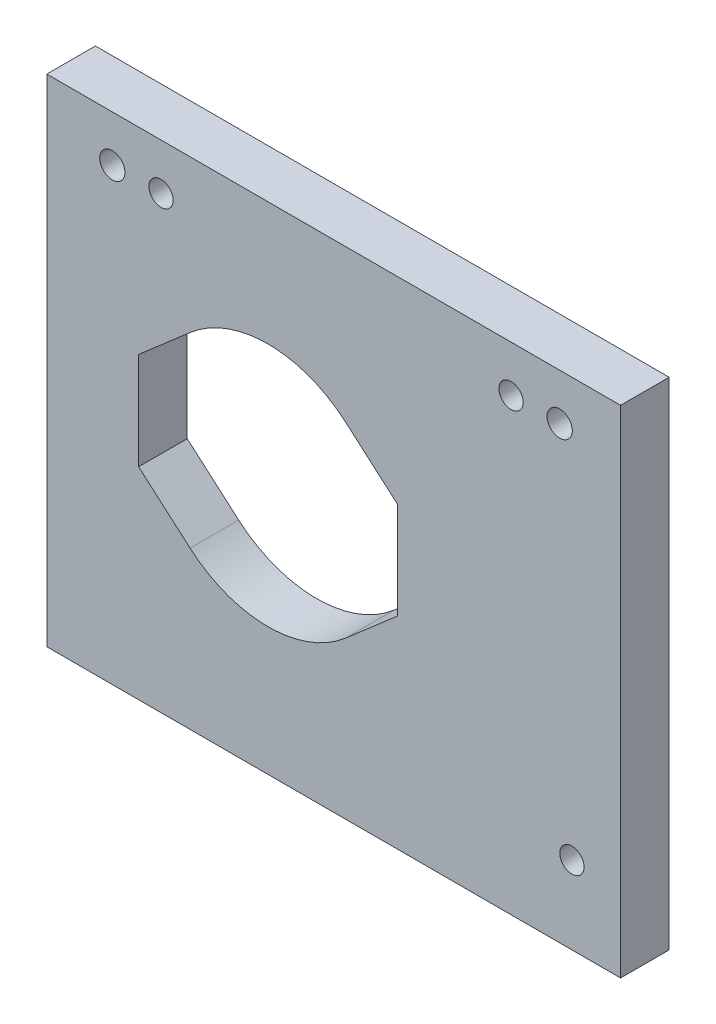
SolidWorks part; units mm, degrees
ref_plane "Alzado" through (0, 0, 0) normal (0, 0, 1) x (1, 0, 0)
ref_plane "Planta" through (0, 0, 0) normal (0, 1, 0) x (1, 0, 0)
ref_plane "Vista lateral" through (0, 0, 0) normal (1, 0, 0) x (0, 0, -1)
sketch "Croquis1" plane through (0, 0, 0) normal (0, 0, 1) x (1, 0, 0)
  line L0 (0, 0) -> (0, 20.5)
  line L5 (29.2611, -25.7476) -> (24.2611, -25.7476)
  line L6 (24.2611, -25.7476) -> (24.2611, -17.7476)
  line L7 (18, 20.5) -> (-18, 20.5)
  line L8 (0, 0) -> (-7, 0)
  line L9 (6.3, 0) -> (-20.3, 0)
  line L10 (-20.3, 5) -> (-20.3, -5)
  line L11 (-29.7389, -25.7476) -> (29.2611, -25.7476)
  line L12 (-29.7389, -25.7476) -> (-29.7389, 25.2524)
  line L13 (-29.7389, 25.2524) -> (29.2611, 25.2524)
  line L14 (29.2611, -25.7476) -> (29.2611, 25.2524)
  line L15 (6.3, 5) -> (6.3, -5)
  line L16 (6.3, 5) -> (1.0077, 9.5983)
  line L17 (6.3, -5) -> (1.0077, -9.5983)
  line L18 (-20.3, -5) -> (-15.0077, -9.5983)
  line L19 (-20.3, 5) -> (-15.0077, 9.5983)
  line L20 (-18, 20.5) -> (-23, 20.5)
  line L21 (18, 20.5) -> (23, 20.5)
  circle A3 centre (24.2611, -17.7476) radius 1.25
  circle A4 centre (-18, 20.5) radius 1.25
  circle A5 centre (18, 20.5) radius 1.25
  arc A7 (-15.0077, 9.5983) -> (1.0077, 9.5983) centre (-7, 0.382) cw
  arc A8 (1.0077, -9.5983) -> (-15.0077, -9.5983) centre (-7, -0.382) cw
  circle A9 centre (-23, 20.5) radius 1.3
  circle A10 centre (23, 20.5) radius 1.3
  point P0 (0, 0)
  point P10 (0, 20.5)
  point P11 (-0.2389, 17.2524)
  point P22 (-7, 0)
  point P24 (-20.3, 0)
  point P27 (6.3, 0)
  dimension "D4" = 2.5
  dimension "D5" = 2.5
  dimension "D8" = 8
  dimension "D9" = 2.5
  dimension "D12" = 5
  dimension "D13" = 13.3
  dimension "D16" = 2.6
  dimension "D18" = 2.6
  dimension "D2" = 20.5
  dimension "D3" = 18
  dimension "D6" = 7
  dimension "D7" = 5
  dimension "D10" = 51
  dimension "D11" = 59
  dimension "D14" = 5
  dimension "D15" = 5
  dimension "D17" = 5
extrude "Saliente-Extruir1" add sketch "Croquis1" along normal blind 5
